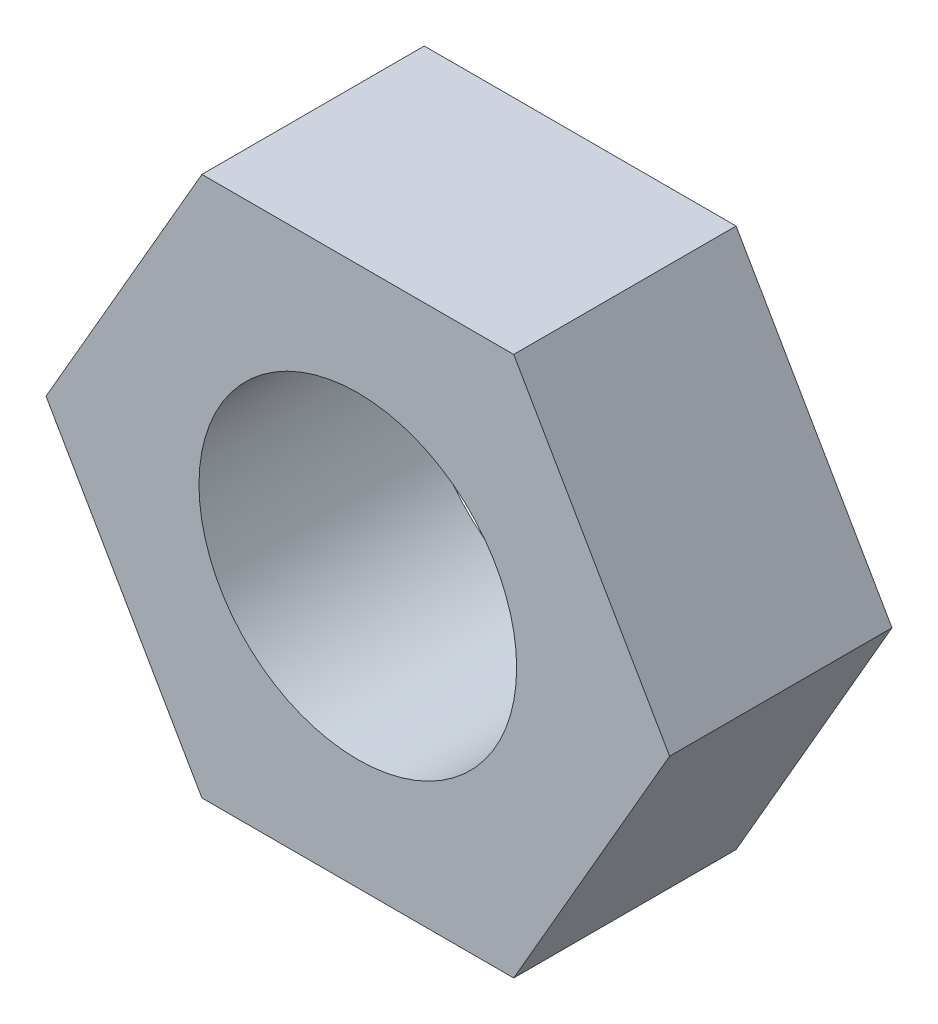
SolidWorks part; units mm, degrees
ref_plane "Plan de face" through (0, 0, 0) normal (0, 0, 1) x (1, 0, 0)
ref_plane "Plan de dessus" through (0, 0, 0) normal (0, 1, 0) x (1, 0, 0)
ref_plane "Plan de droite" through (0, 0, 0) normal (1, 0, 0) x (0, 0, -1)
sketch "Esquisse1" plane through (0, 0, 0) normal (0, 0, 1) x (1, 0, 0)
  line L0 (0, 0) -> (12.4287, 0) construction
  line L1 (9.815, 0) -> (4.9075, 8.5)
  line L2 (4.9075, 8.5) -> (-4.9075, 8.5)
  line L3 (-4.9075, 8.5) -> (-9.815, 0)
  line L4 (-9.815, 0) -> (-4.9075, -8.5)
  line L5 (-4.9075, -8.5) -> (4.9075, -8.5)
  line L6 (4.9075, -8.5) -> (9.815, 0)
  circle A0 centre (0, 0) radius 8.5 construction
  circle A1 centre (0, 0) radius 5
  dimension "D2" = 10
  dimension "D1" = 17
extrude "Boss.-Extru.1" add sketch "Esquisse1" along normal blind 7
